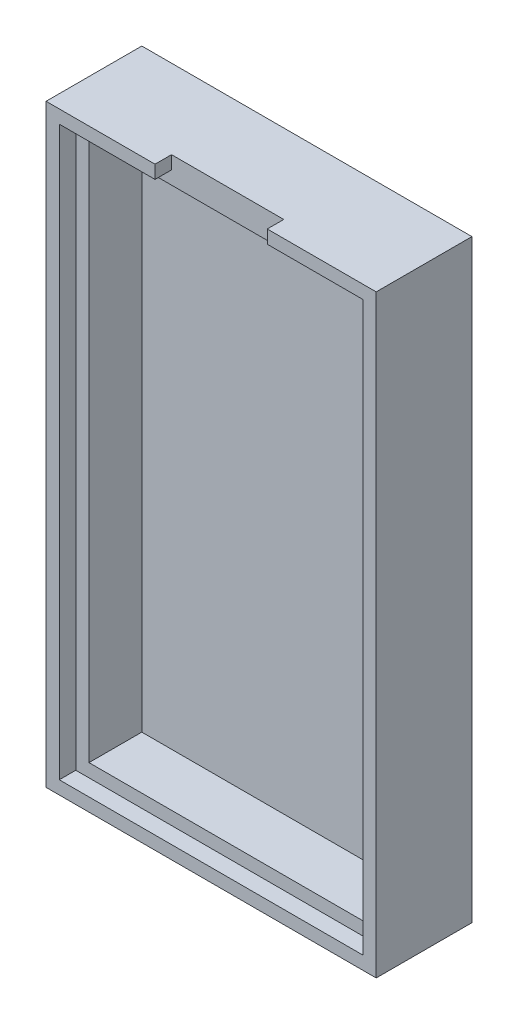
SolidWorks part; units mm, degrees
ref_plane "Front Plane" through (0, 0, 0) normal (0, 0, 1) x (1, 0, 0)
ref_plane "Top Plane" through (0, 0, 0) normal (0, 1, 0) x (1, 0, 0)
ref_plane "Right Plane" through (0, 0, 0) normal (1, 0, 0) x (0, 0, -1)
sketch "Sketch1" plane through (0, 0, 0) normal (0, 0, 1) x (1, 0, 0)
  line L1 (-15.875, 28.575) -> (15.875, 28.575)
  line L2 (-15.875, 28.575) -> (-15.875, -28.575)
  line L3 (-15.875, -28.575) -> (15.875, -28.575)
  line L4 (15.875, 28.575) -> (15.875, -28.575)
  point P4 (0, 28.575)
  point P6 (-15.875, 0)
  dimension "D1" = 57.15
  dimension "D2" = 31.75
extrude "Boss-Extrude1" add sketch "Sketch1" along normal mid plane 9.2075
shell "Shell1" thickness 2.54
sketch "Sketch2" plane through (0, 28.575, 0) normal (0, 1, 0) x (1, 0, 0)
  line L0 (15.875, -4.6037) -> (-15.875, -4.6037) construction
  line L1 (-5.3975, -4.6037) -> (5.3975, -4.6037)
  line L2 (-5.3975, -4.6037) -> (-5.3975, -3.0162)
  line L3 (-5.3975, -3.0162) -> (5.3975, -3.0162)
  line L4 (5.3975, -4.6037) -> (5.3975, -3.0162)
  point P6 (0, -3.0162)
  dimension "D1" = 10.795
  dimension "D2" = 1.5875
extrude "Cut-Extrude1" cut sketch "Sketch2" against normal up to surface (2.54 mm away) up to face at (0, 26.035, 1.27)
sketch "Sketch3" plane through (0, 0, 4.6037) normal (0, 0, 1) x (1, 0, 0)
  line L17 (14.605, -27.305) -> (14.605, 27.305)
  line L18 (-14.605, -27.305) -> (14.605, -27.305)
  line L19 (-14.605, 27.305) -> (-14.605, -27.305)
  line L20 (14.605, 27.305) -> (-14.605, 27.305)
  line L21 (14.605, -27.305) -> (14.605, 27.305)
  line L22 (-14.605, -27.305) -> (14.605, -27.305)
  line L23 (-14.605, 27.305) -> (-14.605, -27.305)
  line L24 (14.605, 27.305) -> (-14.605, 27.305)
  dimension "D1" = 1.27
extrude "Cut-Extrude2" cut sketch "Sketch3" against normal up to surface (1.5875 mm away) up to face at (0, 27.305, 3.0162)
